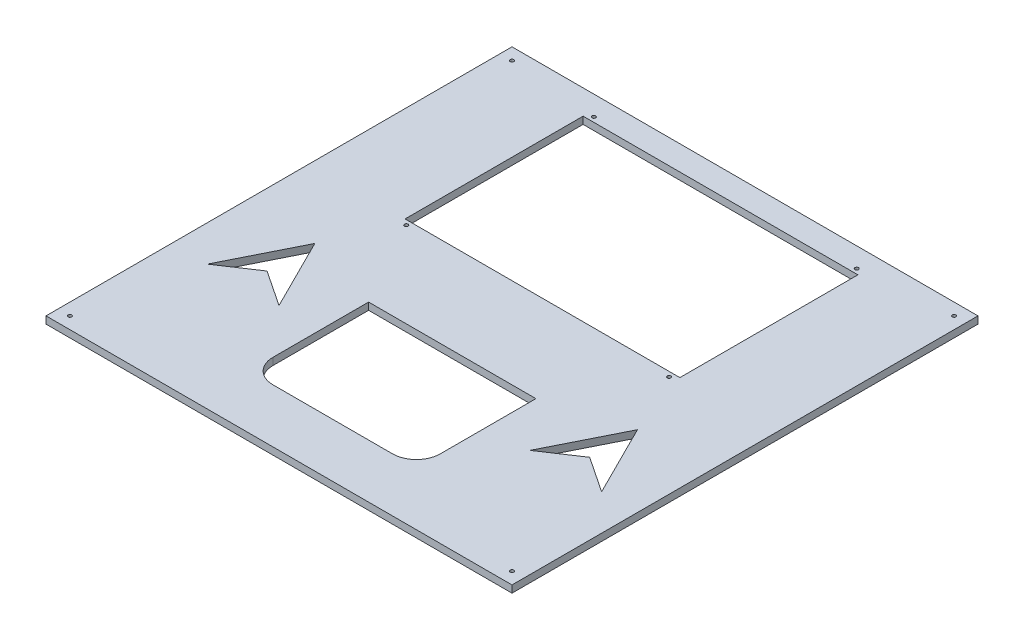
SolidWorks part; units mm, degrees
material "有机玻璃 (TM) GS 丙烯酸铸钣"
ref_plane "前视基准面" through (0, 0, 0) normal (0, 0, 1) x (1, 0, 0)
ref_plane "上视基准面" through (0, 0, 0) normal (0, 1, 0) x (1, 0, 0)
ref_plane "右视基准面" through (0, 0, 0) normal (1, 0, 0) x (0, 0, -1)
other "Configuration Table"
sketch "草图1" plane through (0, 0, 0) normal (0, 1, 0) x (1, 0, 0)
  line L0 (0, 0) -> (0, 100) construction
  line L5 (-195, 195) -> (195, 195)
  line L6 (-195, 195) -> (-195, -195)
  line L7 (-195, -195) -> (195, -195)
  line L8 (195, 195) -> (195, -195)
  line L9 (-195, 195) -> (195, -195) construction
  line L10 (-195, -195) -> (195, 195) construction
  line L11 (-115, 174.5) -> (115, 174.5)
  line L12 (-115, 174.5) -> (-115, 25.5)
  line L13 (-115, 25.5) -> (115, 25.5)
  line L14 (115, 174.5) -> (115, 25.5)
  line L15 (-115, 174.5) -> (115, 25.5) construction
  line L16 (-115, 25.5) -> (115, 174.5) construction
  line L17 (0, 0) -> (0, -100) construction
  line L18 (-110, 178.5) -> (-110, 175.974) construction
  line L19 (-50, -150) -> (50, -150)
  line L20 (-70, -130) -> (-70, -50)
  line L21 (-70, -50) -> (70, -50)
  line L22 (70, -130) -> (70, -50)
  line L23 (-70, -150) -> (70, -50) construction
  line L24 (-70, -50) -> (70, -150) construction
  line L25 (-115, 100) -> (115, 100) construction
  line L26 (-110, 21.5) -> (-110, 24.026) construction
  line L27 (110, 21.5) -> (110, 24.026) construction
  line L28 (110, 178.5) -> (110, 175.974) construction
  line L29 (-179.1124, 0) -> (0, 0) construction
  line L30 (-165, -90) -> (-135, -30)
  line L31 (-135, -30) -> (-135, -115.5704) construction
  line L32 (-165, -90) -> (-135, -70)
  line L33 (-105, -90) -> (-135, -70)
  line L34 (-105, -90) -> (-135, -30)
  line L35 (105, -90) -> (135, -30)
  line L36 (105, -90) -> (135, -70)
  line L37 (165, -90) -> (135, -70)
  line L38 (165, -90) -> (135, -30)
  circle A0 centre (-110, 178.5) radius 1.5
  circle A1 centre (-110, 21.5) radius 1.5
  circle A2 centre (110, 21.5) radius 1.5
  circle A3 centre (110, 178.5) radius 1.5
  circle A4 centre (-185, 185) radius 1.5
  circle A5 centre (-185, -185) radius 1.5
  circle A6 centre (185, -185) radius 1.5
  circle A7 centre (185, 185) radius 1.5
  arc A8 (-50, -150) -> (-70, -130) centre (-50, -130) cw
  arc A9 (50, -150) -> (70, -130) centre (50, -130) ccw
  point P0 (0, 0)
  point P5 (0, 100)
  dimension "D1" = 390
  dimension "D4" = 230
  dimension "D5" = 149
  dimension "D12" = 3
  dimension "D9" = 3
  dimension "D11" = 5
  dimension "D20" = 20
  dimension "D21" = 20
  dimension "D2" = 390
  dimension "D3" = 100
  dimension "D6" = 140
  dimension "D8" = 100
  dimension "D10" = 4
  dimension "D7" = 100
  dimension "D13" = 10
  dimension "D14" = 10
  dimension "D15" = 40
  dimension "D16" = 30
  dimension "D17" = 20
  dimension "D18" = 60
  dimension "D19" = 30
extrude "顶图" add sketch "草图1" along normal blind 6
